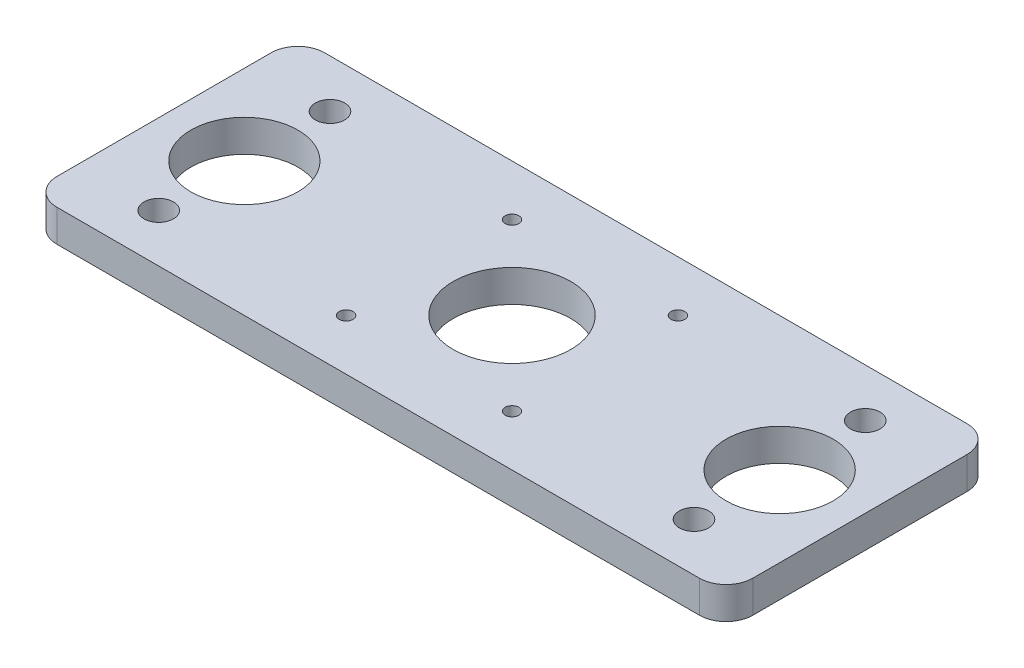
SolidWorks part; units mm, degrees
ref_plane "前视基准面" through (0, 0, 0) normal (0, 0, 1) x (1, 0, 0)
ref_plane "上视基准面" through (0, 0, 0) normal (0, 1, 0) x (1, 0, 0)
ref_plane "右视基准面" through (0, 0, 0) normal (1, 0, 0) x (0, 0, -1)
sketch "草图1" plane through (0, 0, 0) normal (0, 1, 0) x (1, 0, 0)
  line L2 (0, 25) -> (60, 25)
  line L3 (65, 20) -> (65, -20)
  line L4 (60, -25) -> (-60, -25)
  line L5 (-65, -20) -> (-65, 20)
  line L6 (-60, 25) -> (0, 25)
  circle A0 centre (0, 0) radius 11
  circle A1 centre (0, 0) radius 4.5
  circle A2 centre (15.5, 15.5) radius 1.2836
  circle A3 centre (15.5, -15.5) radius 1.2836
  circle A4 centre (-15.5, -15.5) radius 1.2836
  circle A5 centre (-15.5, 15.5) radius 1.2836
  circle A6 centre (50, 0) radius 10
  circle A7 centre (50, 16) radius 2.75
  circle A8 centre (50, -16) radius 2.75
  circle A9 centre (-50, -16) radius 2.75
  circle A10 centre (-50, 16) radius 2.75
  circle A11 centre (-50, 0) radius 10
  arc A12 (-60, -25) -> (-65, -20) centre (-60, -20) cw
  arc A13 (60, -25) -> (65, -20) centre (60, -20) ccw
  arc A14 (65, 20) -> (60, 25) centre (60, 20) ccw
  arc A15 (-65, 20) -> (-60, 25) centre (-60, 20) cw
  point P16 (0, 0)
  dimension "D1" = 4
  dimension "D2" = 50
  dimension "D4" = 5
  dimension "D3" = 32
  dimension "D5" = 50
extrude "凸台-拉伸1" add sketch "草图1" along normal blind 6 contours A15 L5 A12 L4 A13 L3 A14 L2 L6 A10 A0 A2 A3 A4 A5 A6 A7 A8 A9 A11
